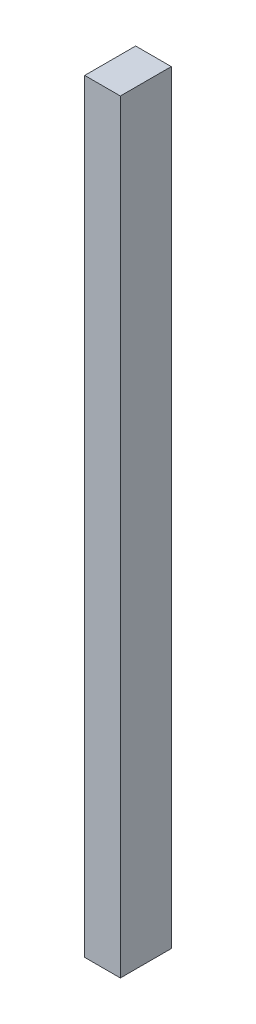
SolidWorks part; units mm, degrees
ref_plane "Front Plane" through (0, 0, 0) normal (0, 0, 1) x (1, 0, 0)
ref_plane "Top Plane" through (0, 0, 0) normal (0, 1, 0) x (1, 0, 0)
ref_plane "Right Plane" through (0, 0, 0) normal (1, 0, 0) x (0, 0, -1)
sketch "Sketch3" plane through (0, 0, 0) normal (1, 0, 0) x (0, 0, -1)
  line L1 (-50, 750) -> (50, 750)
  line L2 (-50, 750) -> (-50, -750)
  line L3 (-50, -750) -> (50, -750)
  line L4 (50, 750) -> (50, -750)
  line L5 (0, 0) -> (50, -750) construction
  line L6 (-50, -750) -> (0, 0) construction
  point P0 (0, 0)
  dimension "D1" = 100
  dimension "D2" = 1500
extrude "Boss-Extrude2" add sketch "Sketch3" along normal blind 70
sketch "Sketch7" plane through (0, 0, 0) normal (1, 0, 0) x (0, 0, -1)
  line L0 (0, 500) -> (0, -500) construction
  line L1 (20, 500) -> (20, -500)
  line L2 (-20, 500) -> (-20, -500)
  arc A0 (20, 500) -> (-20, 500) centre (0, 500) ccw
  arc A1 (-20, -500) -> (20, -500) centre (0, -500) ccw
  point P2 (0, 0)
  dimension "D2" = 20
  dimension "D1" = 1000
extrude "Cut-Extrude2" cut sketch "Sketch7" along normal blind 50
